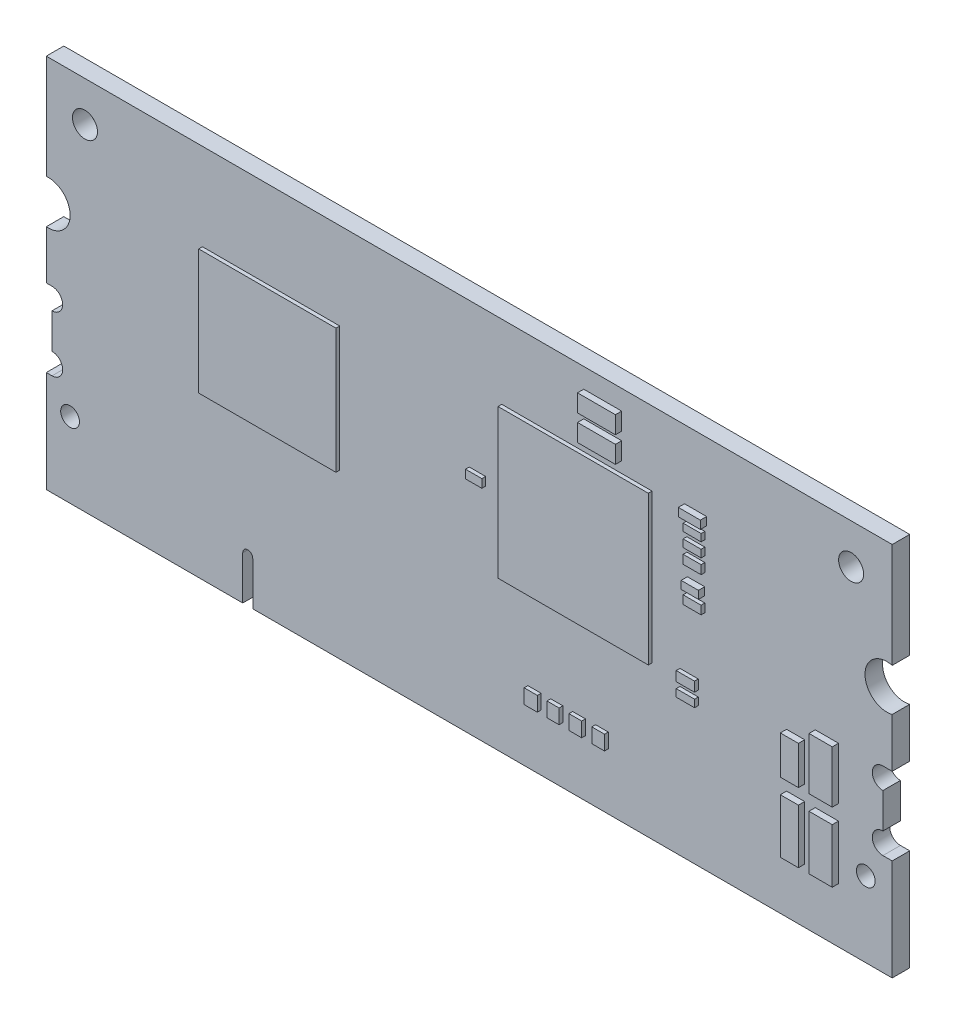
SolidWorks part; units mm, degrees
material "A-Glass Fiber"
ref_plane "Front Plane" through (0, 0, 0) normal (0, 0, 1) x (1, 0, 0)
ref_plane "Top Plane" through (0, 0, 0) normal (0, 1, 0) x (1, 0, 0)
ref_plane "Right Plane" through (0, 0, 0) normal (1, 0, 0) x (0, 0, -1)
sketch "Sketch1" plane through (0, 0, 0) normal (0, 0, 1) x (1, 0, 0)
  line L1 (-33.8, -15) -> (33.8, -15)
  line L2 (-33.8, -15) -> (-33.8, 15)
  line L3 (-33.8, 15) -> (33.8, 15)
  line L4 (33.8, -15) -> (33.8, 15)
  line L5 (-33.8, -15) -> (33.8, 15) construction
  line L6 (-33.8, 15) -> (33.8, -15) construction
  point P0 (0, 0)
  dimension "D1" = 67.6
  dimension "D2" = 30
extrude "Substrate" add sketch "Sketch1" along normal blind 1.4
sketch "Sketch2" plane through (0, 0, 1.4) normal (0, 0, 1) x (1, 0, 0)
  line L0 (-18.1, -15) -> (-18.1, -11.5172)
  line L1 (-33.8, -15) -> (33.8, -15) construction
  line L2 (-18.1, -15) -> (-17.3, -15)
  line L3 (-17.3, -15) -> (-17.3, -11.5172)
  line L4 (31.6875, -8.9912) -> (50031.6875, -8.9912) construction
  line L5 (-30.7191, 11.8046) -> (-50030.7191, 11.8046) construction
  line L6 (33.2956, 4.9364) -> (50033.2956, 4.9364) construction
  line L7 (-33.3412, -6.0575) -> (-33.3412, 49993.9425) construction
  line L8 (33.0572, -5.8561) -> (33.0572, 49994.1439) construction
  line L9 (-33.3412, -6.0476) -> (49966.6588, -6.0476) construction
  line L10 (33.0572, -0.6976) -> (34.6381, -0.6976)
  line L11 (34.6381, -0.6976) -> (34.7108, -6.8976)
  line L12 (34.7108, -6.8976) -> (33.0572, -6.8976)
  line L13 (-33.3412, -5.1976) -> (-33.3412, -2.3976)
  line L14 (-33.3412, -0.6976) -> (-34.3475, -0.6976)
  line L15 (-34.3475, -0.6976) -> (-34.3475, -6.8976)
  line L16 (-34.3475, -6.8976) -> (-33.3412, -6.8976)
  line L17 (-33.8, 15) -> (-33.8, -15) construction
  line L18 (33.0572, -5.1976) -> (33.0572, -2.3976)
  arc A0 (-18.1, -11.5172) -> (-17.3, -11.5172) centre (-17.7, -11.5172) cw
  circle A1 centre (-30.7092, 11.8046) radius 1
  circle A2 centre (30.5169, 11.8046) radius 1
  circle A3 centre (31.6875, -8.9912) radius 0.75
  circle A4 centre (-31.8991, -8.9912) radius 0.75
  circle A5 centre (-33.6436, 4.9364) radius 1.75
  circle A6 centre (33.3761, 4.9364) radius 1.75
  arc A7 (-33.3412, -2.3976) -> (-33.3412, -0.6976) centre (-33.3412, -1.5476) ccw
  arc A8 (-33.3412, -6.8976) -> (-33.3412, -5.1976) centre (-33.3412, -6.0476) ccw
  arc A9 (33.0572, -0.6976) -> (33.0572, -2.3976) centre (33.0572, -1.5476) ccw
  arc A10 (33.0572, -5.1976) -> (33.0572, -6.8976) centre (33.0572, -6.0476) ccw
  dimension "D2" = 3.5
  dimension "D3" = 3.5
  dimension "D4" = 2
  dimension "D5" = 2
  dimension "D6" = 1.5
  dimension "D7" = 1.5
  dimension "D8" = 1.7
  dimension "D9" = 1.7
  dimension "D11" = 1.7
  dimension "D12" = 1.7
  dimension "D1" = 0.8
  dimension "D10" = 4.5
  dimension "D13" = 4.5
  dimension "D14" = 15.7
extrude "Cutouts" cut sketch "Sketch2" against normal blind 2
sketch "Sketch3" plane through (0, 0, 1.4) normal (0, 0, 1) x (1, 0, 0)
  line L1 (14.613, -2.7834) -> (2.604, -2.7834)
  line L2 (14.613, -2.7834) -> (14.613, 9.103)
  line L3 (14.613, 9.103) -> (2.604, 9.103)
  line L4 (2.604, -2.7834) -> (2.604, 9.103)
  line L5 (-10.3503, -1.9299) -> (-21.3212, -1.9299)
  line L6 (-10.3503, -1.9299) -> (-10.3503, 8.0493)
  line L7 (-10.3503, 8.0493) -> (-21.3212, 8.0493)
  line L8 (-21.3212, -1.9299) -> (-21.3212, 8.0493)
extrude "Chips" add sketch "Sketch3" along normal blind 0.3
sketch "Sketch4" plane through (0, 0, 1.4) normal (0, 0, 1) x (1, 0, 0)
  line L1 (9.1525, 13.4246) -> (12.18, 13.4246)
  line L2 (9.1525, 13.4246) -> (9.1525, 12.0329)
  line L3 (9.1525, 12.0329) -> (12.18, 12.0329)
  line L4 (12.18, 13.4246) -> (12.18, 12.0329)
  line L5 (9.1525, 11.3737) -> (12.18, 11.3737)
  line L6 (9.1525, 11.3737) -> (9.1525, 9.982)
  line L7 (9.1525, 9.982) -> (12.18, 9.982)
  line L8 (12.18, 11.3737) -> (12.18, 9.982)
  line L9 (17.2051, 9.5221) -> (18.9661, 9.5221)
  line L10 (17.2051, 9.5221) -> (17.2051, 8.8708)
  line L11 (17.2051, 8.8708) -> (18.9661, 8.8708)
  line L12 (18.9661, 9.5221) -> (18.9661, 8.8708)
  line L13 (25.3588, -5.0724) -> (26.8062, -5.0724)
  line L14 (25.3588, -5.0724) -> (25.3588, -2.0088)
  line L15 (25.3588, -2.0088) -> (26.8062, -2.0088)
  line L16 (26.8062, -5.0724) -> (26.8062, -2.0088)
  line L17 (27.6505, -0.8991) -> (29.508, -0.8991)
  line L18 (27.6505, -0.8991) -> (27.6505, -5.0724)
  line L19 (27.6505, -5.0724) -> (29.508, -5.0724)
  line L20 (29.508, -0.8991) -> (29.508, -5.0724)
  line L21 (29.508, -10.6166) -> (27.6505, -10.6166)
  line L22 (29.508, -10.6166) -> (29.508, -6.2851)
  line L23 (29.508, -6.2851) -> (27.6505, -6.2851)
  line L24 (27.6505, -10.6166) -> (27.6505, -6.2851)
  line L25 (25.3588, -6.2851) -> (26.8062, -6.2851)
  line L26 (25.3588, -6.2851) -> (25.3588, -10.6166)
  line L27 (25.3588, -10.6166) -> (26.8062, -10.6166)
  line L28 (26.8062, -6.2851) -> (26.8062, -10.6166)
  line L29 (17.4347, 4.5857) -> (18.8151, 4.5857)
  line L30 (17.4347, 4.5857) -> (17.4347, 3.9599)
  line L31 (17.4347, 3.9599) -> (18.8151, 3.9599)
  line L32 (18.8151, 4.5857) -> (18.8151, 3.9599)
extrude "Capacitors" add sketch "Sketch4" along normal blind 0.5
sketch "Sketch5" plane through (0, 0, 1.4) normal (0, 0, 1) x (1, 0, 0)
  line L1 (17.3918, 7.8452) -> (18.8287, 7.8452)
  line L2 (17.3918, 7.8452) -> (17.3918, 8.4246)
  line L3 (17.3918, 8.4246) -> (18.8287, 8.4246)
  line L4 (18.8287, 7.8452) -> (18.8287, 8.4246)
  line L5 (18.8287, 7.3353) -> (17.3918, 7.3353)
  line L6 (18.8287, 7.3353) -> (18.8287, 6.7328)
  line L7 (18.8287, 6.7328) -> (17.3918, 6.7328)
  line L8 (17.3918, 7.3353) -> (17.3918, 6.7328)
  line L9 (17.3918, 6.2693) -> (18.8287, 6.2693)
  line L10 (17.3918, 6.2693) -> (17.3918, 5.574)
  line L11 (17.3918, 5.574) -> (18.8287, 5.574)
  line L12 (18.8287, 6.2693) -> (18.8287, 5.574)
  line L13 (18.8287, 2.7929) -> (17.3918, 2.7929)
  line L14 (18.8287, 2.7929) -> (18.8287, 3.465)
  line L15 (18.8287, 3.465) -> (17.3918, 3.465)
  line L16 (17.3918, 2.7929) -> (17.3918, 3.465)
  line L17 (16.8392, -3.8962) -> (18.3047, -3.8962)
  line L18 (16.8392, -3.8962) -> (16.8392, -3.3009)
  line L19 (16.8392, -3.3009) -> (18.3047, -3.3009)
  line L20 (18.3047, -3.8962) -> (18.3047, -3.3009)
  line L21 (0, 2.7929) -> (1.3051, 2.7929)
  line L22 (0, 2.7929) -> (0, 3.465)
  line L23 (0, 3.465) -> (1.3051, 3.465)
  line L24 (1.3051, 2.7929) -> (1.3051, 3.465)
  line L25 (16.8392, -2.0536) -> (18.3047, -2.0536)
  line L26 (16.8392, -2.0536) -> (16.8392, -2.8242)
  line L27 (16.8392, -2.8242) -> (18.3047, -2.8242)
  line L28 (18.3047, -2.0536) -> (18.3047, -2.8242)
extrude "Resistors" add sketch "Sketch5" along normal blind 0.3
sketch "Sketch6" plane through (0, 0, 1.4) normal (0, 0, 1) x (1, 0, 0)
  line L1 (4.6854, -10.4855) -> (5.7413, -10.4855)
  line L2 (4.6854, -10.4855) -> (4.6854, -9.3222)
  line L3 (4.6854, -9.3222) -> (5.7413, -9.3222)
  line L4 (5.7413, -10.4855) -> (5.7413, -9.3222)
  line L5 (6.5108, -9.3222) -> (7.4773, -9.3222)
  line L6 (6.5108, -9.3222) -> (6.5108, -10.4855)
  line L7 (6.5108, -10.4855) -> (7.4773, -10.4855)
  line L8 (7.4773, -9.3222) -> (7.4773, -10.4855)
  line L9 (8.2647, -9.3222) -> (9.2848, -9.3222)
  line L10 (8.2647, -9.3222) -> (8.2647, -10.4855)
  line L11 (8.2647, -10.4855) -> (9.2848, -10.4855)
  line L12 (9.2848, -9.3222) -> (9.2848, -10.4855)
  line L13 (10.0902, -9.3222) -> (11.1103, -9.3222)
  line L14 (10.0902, -9.3222) -> (10.0902, -10.4855)
  line L15 (10.0902, -10.4855) -> (11.1103, -10.4855)
  line L16 (11.1103, -9.3222) -> (11.1103, -10.4855)
extrude "L Component" add sketch "Sketch6" along normal blind 0.3
sketch "Sketch7" plane through (0, 0, 1.4) normal (0, 0, 1) x (1, 0, 0)
  line L0 (-18.1, -15) -> (-18.1, -11.1172) construction
  dimension "D1" = 3.8828
